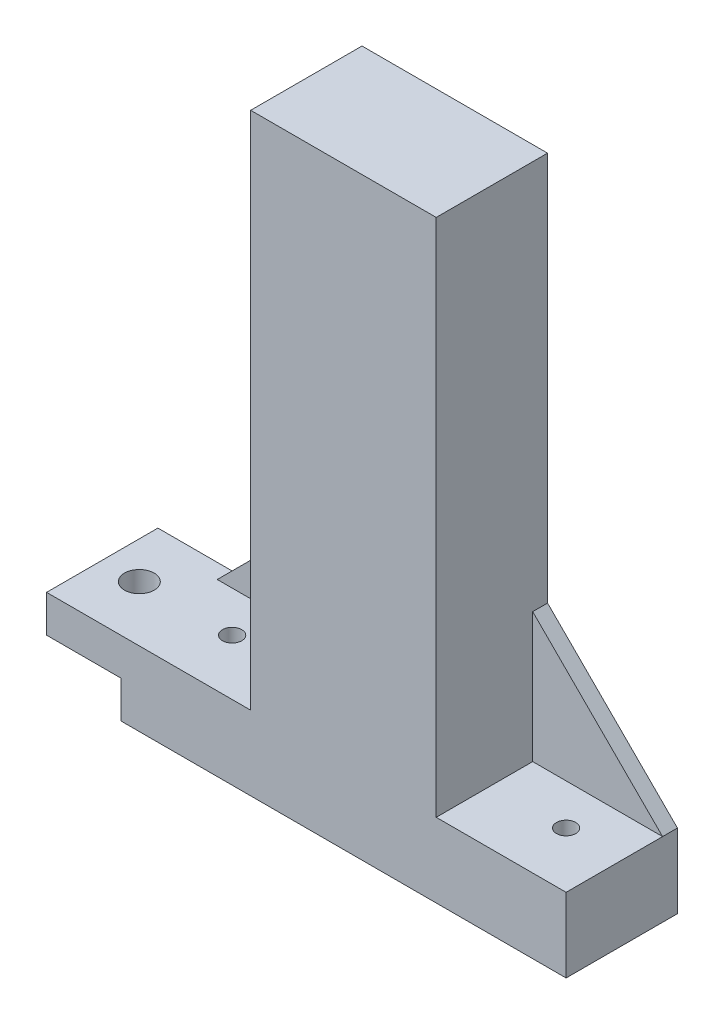
SolidWorks part; units mm, degrees
ref_plane "前基準面" through (0, 0, 0) normal (0, 0, 1) x (1, 0, 0)
ref_plane "上基準面" through (0, 0, 0) normal (0, 1, 0) x (1, 0, 0)
ref_plane "右基準面" through (0, 0, 0) normal (1, 0, 0) x (0, 0, -1)
sketch "草圖2" plane through (0, 0, 0) normal (0, 1, 0) x (1, 0, 0)
  line L5 (-30, 7.5) -> (30, 7.5)
  line L6 (-30, 7.5) -> (-30, -7.5)
  line L7 (-30, -7.5) -> (30, -7.5)
  line L8 (30, 7.5) -> (30, -7.5)
  line L9 (0, -7.5) -> (0, 7.5) construction
  line L10 (-30, 0) -> (30, 0) construction
  circle A4 centre (-22.5, 0) radius 1.3
  circle A5 centre (22.5, 0) radius 1.3
  point P0 (0, 0)
  dimension "D3" = 45
  dimension "D2" = 2.6
  dimension "D1" = 60
  dimension "D4" = 15
extrude "填料-伸長1" add sketch "草圖2" along normal blind 10
sketch "草圖3" plane through (0, 10, 0) normal (0, 1, 0) x (1, 0, 0)
  line L0 (-30, -7.5) -> (30, -7.5) construction
  line L1 (-12.5, 7.5) -> (12.5, 7.5)
  line L2 (-12.5, 7.5) -> (-12.5, -7.5)
  line L3 (-12.5, -7.5) -> (12.5, -7.5)
  line L4 (12.5, 7.5) -> (12.5, -7.5)
  line L5 (0, -7.5) -> (0, 7.5) construction
  line L6 (-12.5, 0) -> (12.5, 0) construction
  point P0 (0, 0)
  point P6 (-22.5, 0)
  point P7 (22.5, 0)
  dimension "D1" = 25
  dimension "D2" = 10
extrude "填料-伸長2" add sketch "草圖3" along normal blind 70
sketch "草圖5" plane through (0, 0, -7.5) normal (0, 0, -1) x (-1, 0, 0)
  line L0 (-30, 10) -> (-12.5, 27.5)
  line L1 (-12.5, 80) -> (-12.5, 10) construction
  line L2 (-12.5, 27.5) -> (-12.5, 10)
  line L3 (-12.5, 10) -> (-30, 10)
  line L4 (0, 0) -> (0, 43.0538) construction
  line L5 (-30, 0) -> (30, 0) construction
  line L6 (12.5, 27.5) -> (12.5, 10)
  line L7 (30, 10) -> (12.5, 27.5)
  line L8 (12.5, 10) -> (30, 10)
  dimension "D1" = 45
extrude "填料-伸長3" add sketch "草圖5" against normal blind 2
sketch "草圖6" plane through (0, 0, 7.5) normal (0, 0, 1) x (1, 0, 0)
  line L1 (-30, 10) -> (-40, 10)
  line L2 (-30, 10) -> (-30, 5)
  line L3 (-30, 5) -> (-40, 5)
  line L4 (-40, 10) -> (-40, 5)
  dimension "D1" = 10
  dimension "D2" = 5
extrude "填料-伸長4" add sketch "草圖6" against normal up to surface (15 mm away) up to face at (0, 29.375, -7.5)
sketch "草圖7" plane through (0, 10, 0) normal (0, 1, 0) x (1, 0, 0)
  line L0 (-40, 7.5) -> (-40, -7.5) construction
  circle A0 centre (-35, 0) radius 2
  point P4 (-35, 0)
  point P5 (0, 0)
  dimension "D1" = 5
  dimension "D2" = 4
extrude "除料-伸長1" cut sketch "草圖7" against normal through all
